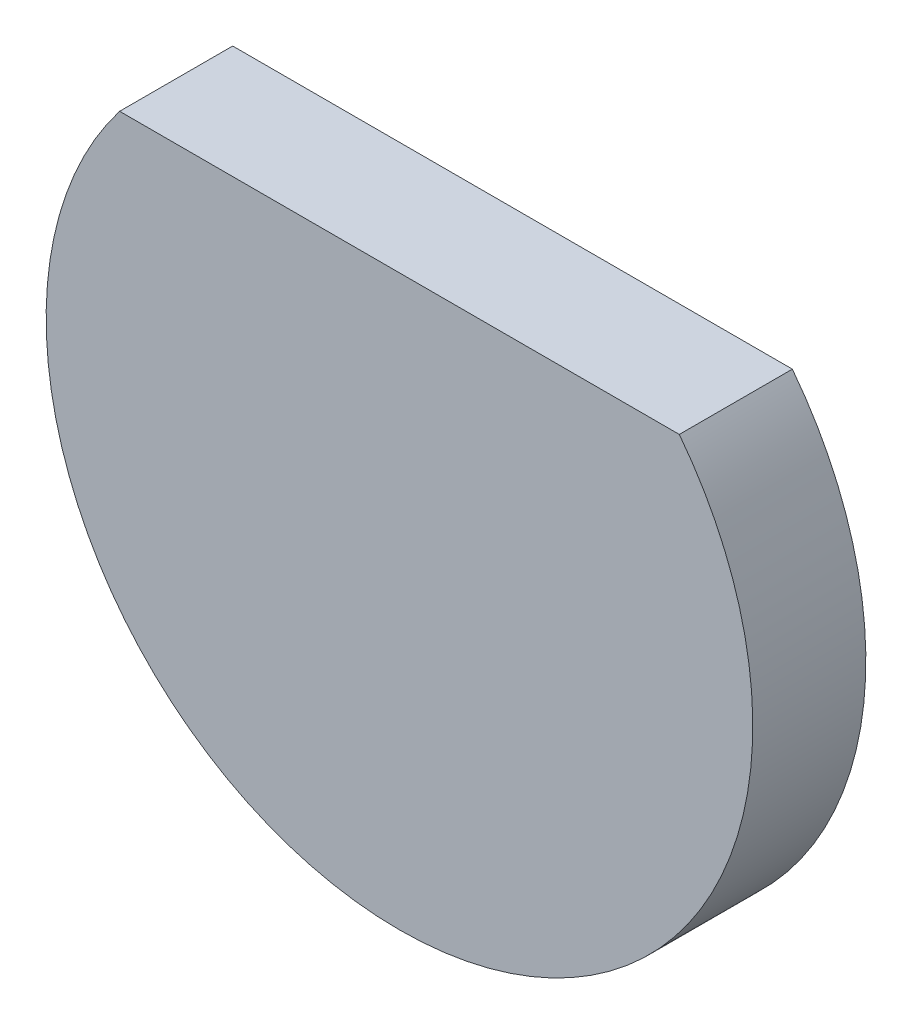
SolidWorks part; units mm, degrees
ref_plane "Front Plane" through (0, 0, 0) normal (0, 0, 1) x (1, 0, 0)
ref_plane "Top Plane" through (0, 0, 0) normal (0, 1, 0) x (1, 0, 0)
ref_plane "Right Plane" through (0, 0, 0) normal (1, 0, 0) x (0, 0, -1)
sketch "Sketch1" plane through (0, 0, 0) normal (0, 0, 1) x (1, 0, 0)
  line L0 (-49.5, 38.1576) -> (49.5, 38.1576)
  arc A0 (-49.5, 38.1576) -> (49.5, 38.1576) centre (0, 0) ccw
  dimension "D1" = 99
  dimension "D2" = 125
extrude "Boss-Extrude1" add sketch "Sketch1" along normal blind 20
